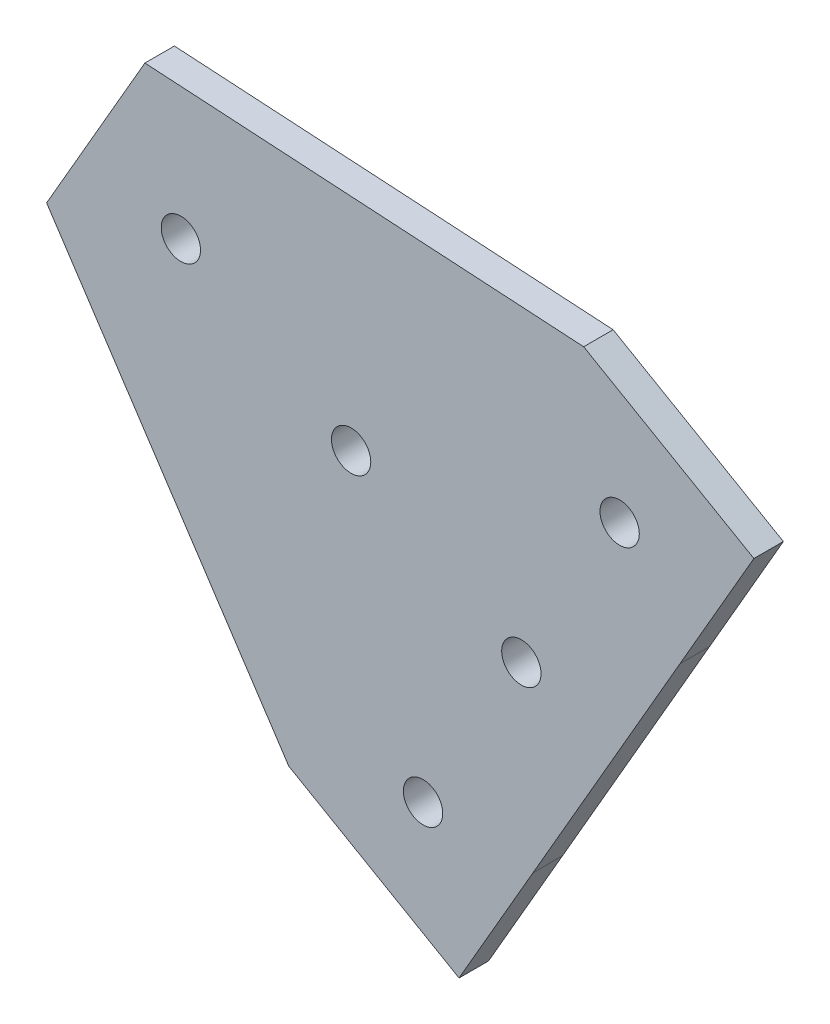
SolidWorks part; units mm, degrees
ref_plane "前视基准面" through (0, 0, 0) normal (0, 0, 1) x (1, 0, 0)
ref_plane "上视基准面" through (0, 0, 0) normal (0, 1, 0) x (1, 0, 0)
ref_plane "右视基准面" through (0, 0, 0) normal (1, 0, 0) x (0, 0, -1)
sketch "草图1" plane through (0, 0, 0) normal (0, 0, 1) x (1, 0, 0)
  line L0 (-23.1177, -59.7875) -> (-8.2108, -33.9679)
  line L1 (-8.165, -33.8869) -> (-0.665, -20.8965)
  line L2 (-0.665, -20.8965) -> (-17.9855, -10.8965)
  line L3 (-17.9855, -10.8965) -> (-62.6265, -8.217)
  line L4 (-62.6265, -8.217) -> (-72.6265, -25.5375)
  line L5 (-72.6265, -25.5375) -> (-47.9855, -62.858)
  line L6 (-47.9855, -62.858) -> (-30.665, -72.858)
  line L7 (-30.665, -72.858) -> (-23.165, -59.8677)
  circle A0 centre (-58.9663, -21.8773) radius 2
  circle A1 centre (-41.6458, -31.8773) radius 2
  arc A2 (-23.1177, -59.7875) -> (-23.165, -59.8677) centre (-18.8349, -62.3677) ccw
  arc A3 (-8.165, -33.8869) -> (-8.2108, -33.9679) centre (-3.8349, -36.3869) ccw
  circle A4 centre (-24.3253, -41.8773) radius 2
  circle A5 centre (-14.3253, -24.5568) radius 2
  circle A6 centre (-34.3253, -59.1978) radius 2
  dimension "D1" = 4
extrude "凸台-拉伸1" add sketch "草图1" along normal blind 3
